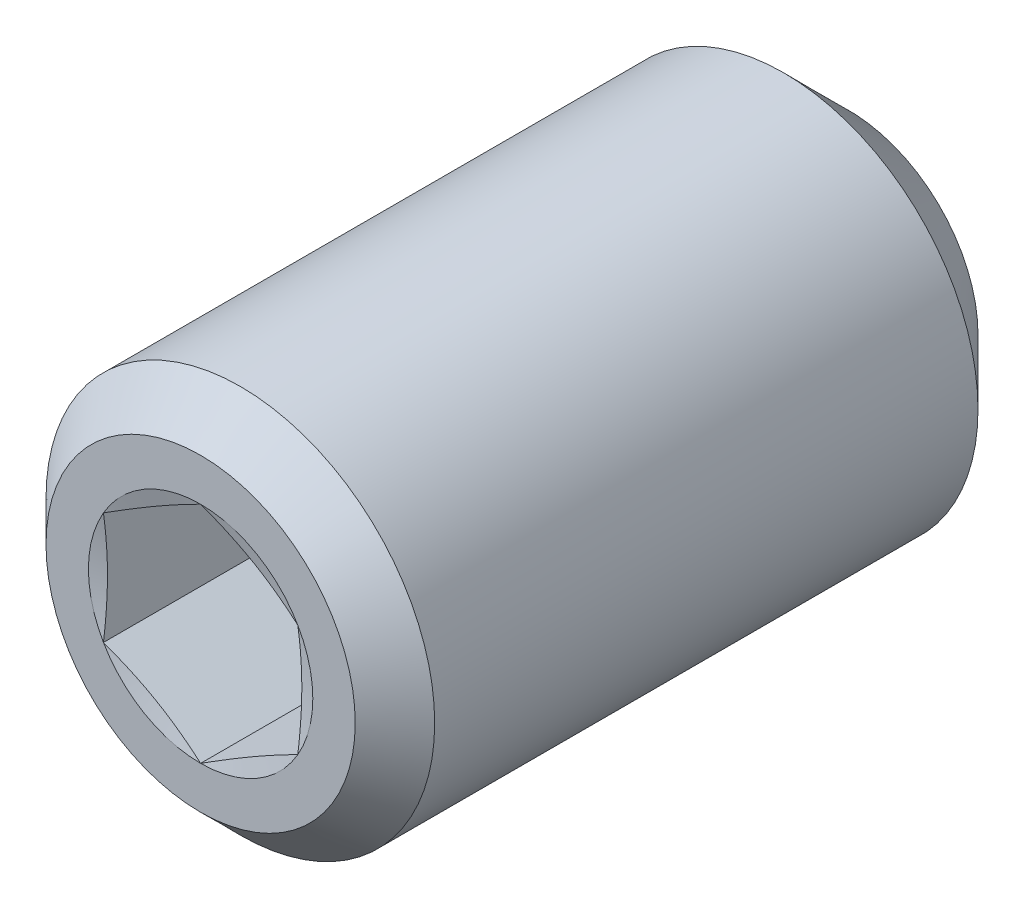
SolidWorks part; units mm, degrees
ref_plane "Front Plane" through (0, 0, 0) normal (0, 0, 1) x (1, 0, 0)
ref_plane "Top Plane" through (0, 0, 0) normal (0, 1, 0) x (1, 0, 0)
ref_plane "Right Plane" through (0, 0, 0) normal (1, 0, 0) x (0, 0, -1)
sketch "Sketch1" plane through (0, 0, 0) normal (1, 0, 0) x (0, 0, -1)
  line L0 (0, 0) -> (19.8153, 0) construction
  line L3 (0.3067, 1.5) -> (4.5, 1.5)
  line L4 (4.5, 1.5) -> (5, 1)
  line L5 (5, 1) -> (5, 0)
  line L8 (0, 0.75) -> (1.2, 0.75)
  line L9 (1.2, 0.75) -> (1.633, 0)
  line L10 (1.633, 0) -> (5, 0)
  line L12 (0, 0.75) -> (0, 1.1933)
  line L13 (0, 1.1933) -> (0.3067, 1.5)
  dimension "D1" = 60
  dimension "S1" = 1.5
  dimension "T1" = 1.2
  dimension "HoleSize" = 3
  dimension "D3" = 45
  dimension "D5" = 45
  dimension "Dp" = 2
  dimension "DF" = 2.3866
  dimension "Length" = 5
revolve "Revolve1" add sketch "Sketch1" angle 360 about L0
cosmetic thread "Cosmetic Thread1" parameters "D2"=3
sketch "Sketch2" plane through (0, 0, 0) normal (0, 0, 1) x (1, 0, 0)
  line L0 (0, 0) -> (0, 0.866) construction
  line L1 (0, 0.866) -> (-0.75, 0.433)
  line L2 (-0.75, 0.433) -> (-0.75, -0.433)
  line L3 (-0.75, -0.433) -> (0, -0.866)
  line L4 (0, -0.866) -> (0.75, -0.433)
  line L5 (0.75, -0.433) -> (0.75, 0.433)
  line L6 (0.75, 0.433) -> (0, 0.866)
  circle A0 centre (0, 0) radius 0.75 construction
  dimension "S2" = 1.5
extrude "Cut-Extrude1" cut sketch "Sketch2" against normal blind 1.2
sketch "Sketch3" plane through (0, 0, 0) normal (1, 0, 0) x (0, 0, -1)
  line L0 (0, 0.75) -> (0, 0.866)
  line L1 (0, 0.866) -> (0.0311, 0.75)
  line L2 (0.0311, 0.75) -> (0, 0.75)
  line L3 (0, 0) -> (2.1263, 0) construction
  dimension "D1" = 15
  dimension "S3" = 1.5
revolve "Cut-Revolve2" cut sketch "Sketch3" angle 360 about L3
